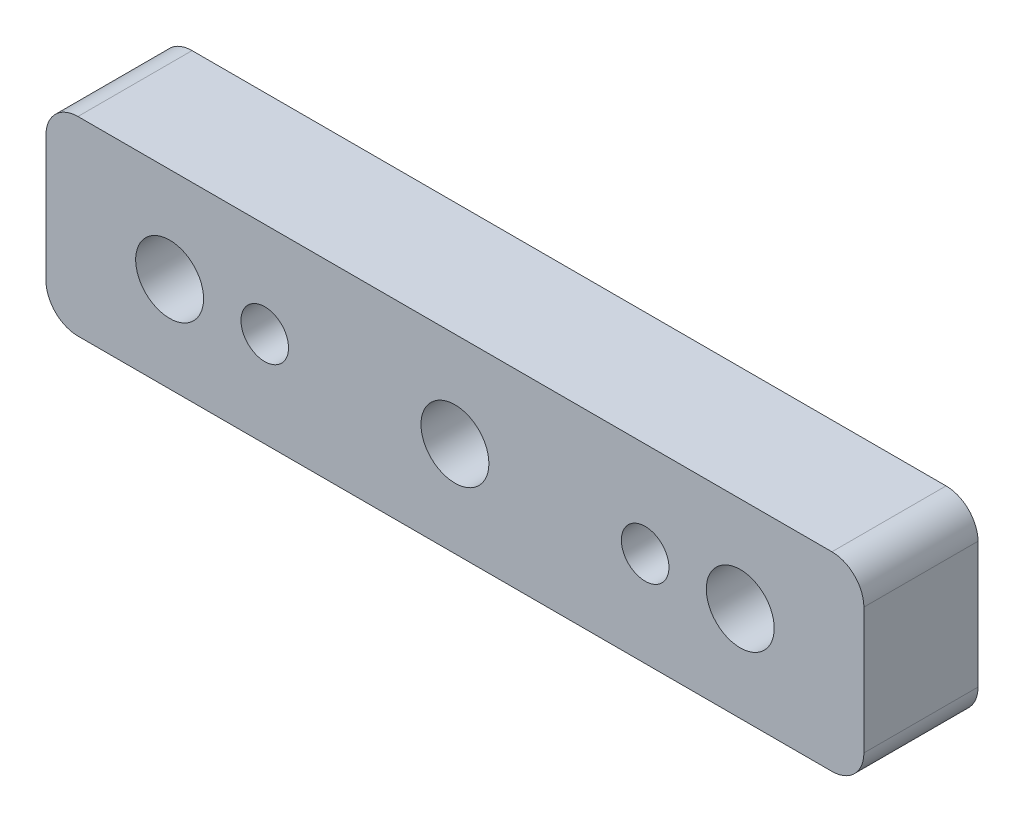
SolidWorks part; units mm, degrees
ref_plane "Plan de face" through (0, 0, 0) normal (0, 0, 1) x (1, 0, 0)
ref_plane "Plan de dessus" through (0, 0, 0) normal (0, 1, 0) x (1, 0, 0)
ref_plane "Plan de droite" through (0, 0, 0) normal (1, 0, 0) x (0, 0, -1)
sketch "Esquisse1" plane through (0, 0, 0) normal (0, 0, 1) x (1, 0, 0)
  line L0 (0, 0) -> (-20, 0) construction
  line L1 (-39.64, -10) -> (39.64, -10)
  line L2 (-43, -6.64) -> (-43, 6.64)
  line L3 (-39.64, 10) -> (39.64, 10)
  line L4 (43, -6.64) -> (43, 6.64)
  line L5 (-43, -10) -> (43, 10) construction
  line L6 (-43, 10) -> (43, -10) construction
  line L7 (-20, 0) -> (20, 0) construction
  circle A0 centre (-30, 0) radius 3.57
  circle A1 centre (0, 0) radius 3.57
  circle A2 centre (30, 0) radius 3.57
  circle A3 centre (-20, 0) radius 2.5
  circle A4 centre (20, 0) radius 2.5
  arc A5 (39.64, 10) -> (43, 6.64) centre (39.64, 6.64) cw
  arc A6 (39.64, -10) -> (43, -6.64) centre (39.64, -6.64) ccw
  arc A7 (-39.64, -10) -> (-43, -6.64) centre (-39.64, -6.64) cw
  arc A8 (-43, 6.64) -> (-39.64, 10) centre (-39.64, 6.64) cw
  point P0 (0, 0)
  dimension "D3" = 7.14
  dimension "D6" = 5
  dimension "D9" = 3.36
  dimension "D1" = 20
  dimension "D2" = 86
  dimension "D4" = 30
  dimension "D7" = 20
  dimension "D5" = 3
  dimension "D8" = 2
extrude "Boss.-Extru.1" add sketch "Esquisse1" along normal mid plane 12
